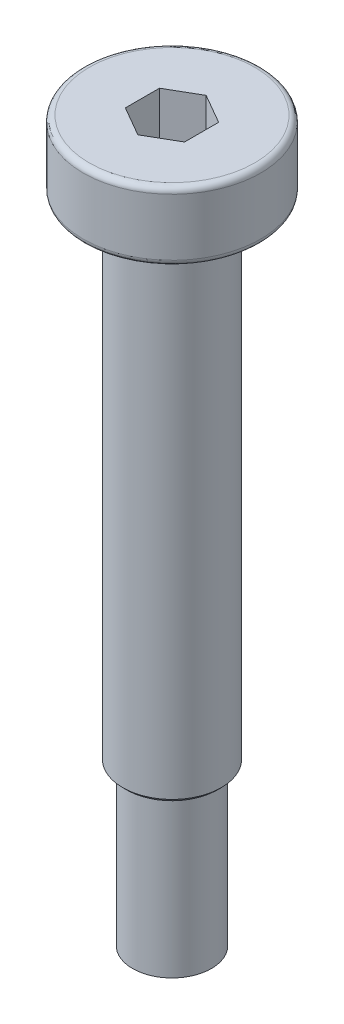
SolidWorks part; units mm, degrees
ref_plane "前视基准面" through (0, 0, 0) normal (0, 0, 1) x (1, 0, 0)
ref_plane "上视基准面" through (0, 0, 0) normal (0, 1, 0) x (1, 0, 0)
ref_plane "右视基准面" through (0, 0, 0) normal (1, 0, 0) x (0, 0, -1)
sketch "草图1" plane through (0, 0, 0) normal (0, 0, 1) x (1, 0, 0)
  line L0 (0, 13.2929) -> (0, -24.3848) construction
  line L1 (0, 9.6164) -> (-4.5, 9.6164)
  line L2 (-4.5, 9.6164) -> (-4.5, 6.1164)
  line L3 (-4.5, 6.1164) -> (-2.5, 6.1164)
  line L4 (-2.5, 6.1164) -> (-2.5, -18.8836)
  line L5 (-2.5, -18.8836) -> (-2, -18.8836)
  line L6 (-2, -18.8836) -> (-2, -26.8836)
  line L7 (-2, -26.8836) -> (0, -26.8836)
  line L8 (0, 9.6164) -> (0, -26.8836)
  dimension "D1" = 4
  dimension "D2" = 8
  dimension "D3" = 5
  dimension "D4" = 9
  dimension "D5" = 3.5
  dimension "D6" = 25
revolve "旋转1" add sketch "草图1" angle 360 about L0
cosmetic thread "装饰螺纹线1" parameters "D2"=3.242
fillet "圆角1" radius 0.3 2 edges at (0, 6.1164, 4.5) (0, 9.6164, 4.5)
sketch "草图2" plane through (0, 9.6164, 0) normal (0, 1, 0) x (1, 0, 0)
  line L1 (1.5, 0.866) -> (0, 1.7321)
  line L2 (0, 1.7321) -> (-1.5, 0.866)
  line L3 (-1.5, 0.866) -> (-1.5, -0.866)
  line L4 (-1.5, -0.866) -> (0, -1.7321)
  line L5 (0, -1.7321) -> (1.5, -0.866)
  line L6 (1.5, -0.866) -> (1.5, 0.866)
  circle A0 centre (0, 0) radius 1.5 construction
  dimension "D1" = 3
extrude "切除-拉伸1" cut sketch "草图2" against normal blind 2.4
chamfer "倒角1" distance 0.2 angle 45 1 edges at (0, -18.8836, 2.5)
